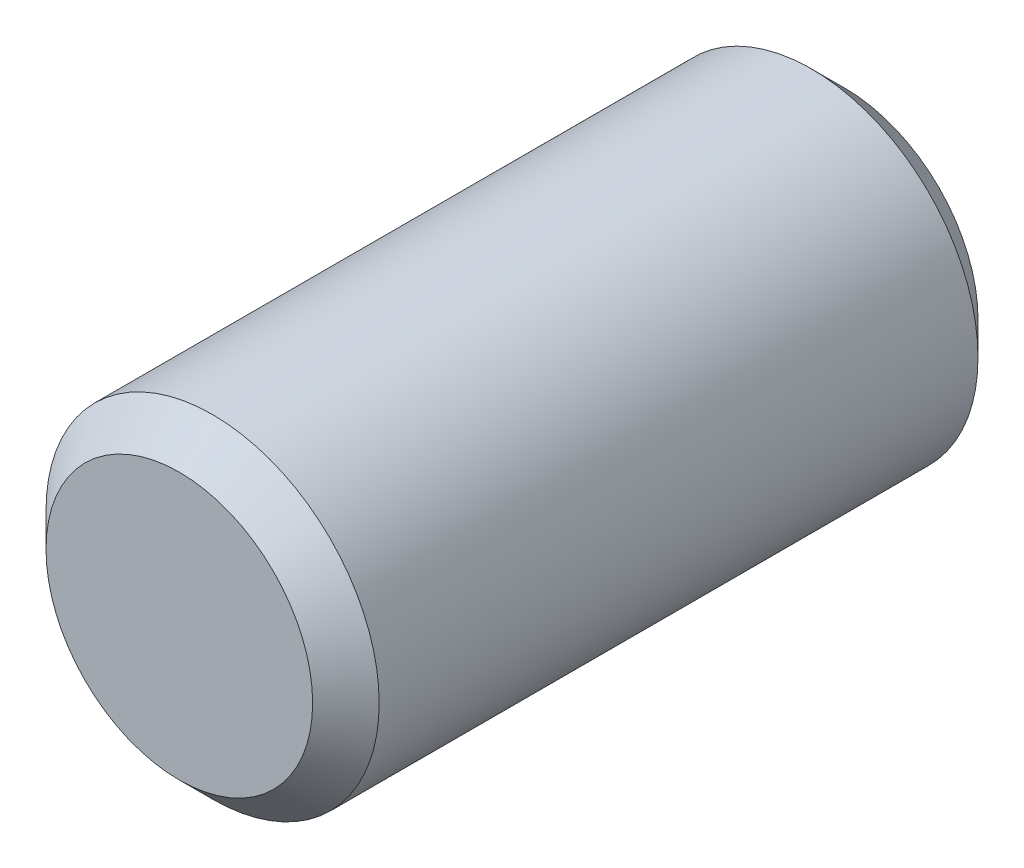
SolidWorks part; units mm, degrees
material "ANSI B18.85 ALLOY STEEL"
ref_plane "Front Plane" through (0, 0, 0) normal (0, 0, 1) x (1, 0, 0)
ref_plane "Top Plane" through (0, 0, 0) normal (0, 1, 0) x (1, 0, 0)
ref_plane "Right Plane" through (0, 0, 0) normal (1, 0, 0) x (0, 0, -1)
sketch "Sketch1" plane through (0, 0, 0) normal (1, 0, 0) x (0, 0, -1)
  line L0 (0, 0) -> (53.164, 0) construction
  line L1 (0, 0) -> (0, 5.0075)
  line L2 (0, 5.0075) -> (20, 5.0075)
  line L3 (20, 5.0075) -> (20, 0)
  line L4 (0, 0) -> (20, 0)
  dimension "D1" = 20
  dimension "D2" = 10.015
revolve "Revolve1" add sketch "Sketch1" angle 360 about L0
chamfer "Chamfer1" distance 1 angle 45 2 edges at (5.0075, 0, -20) (5.0075, 0, 0)
